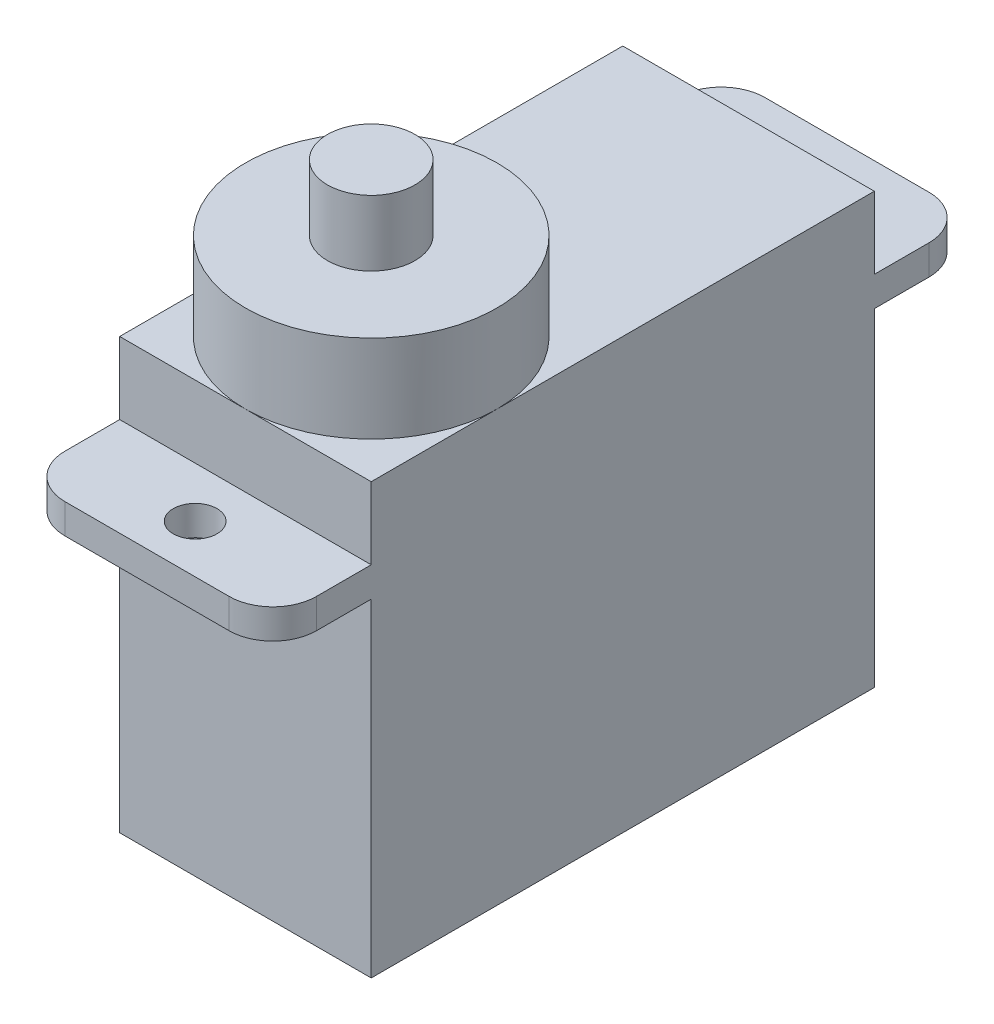
SolidWorks part; units mm, degrees
ref_plane "前视基准面" through (0, 0, 0) normal (0, 0, 1) x (1, 0, 0)
ref_plane "上视基准面" through (0, 0, 0) normal (0, 1, 0) x (1, 0, 0)
ref_plane "右视基准面" through (0, 0, 0) normal (1, 0, 0) x (0, 0, -1)
sketch "草图1" plane through (0, 0, 0) normal (0, 1, 0) x (1, 0, 0)
  line L1 (-5.75, 11.5) -> (5.75, 11.5)
  line L2 (-5.75, 11.5) -> (-5.75, -11.5)
  line L3 (-5.75, -11.5) -> (5.75, -11.5)
  line L4 (5.75, 11.5) -> (5.75, -11.5)
  line L5 (-5.75, 11.5) -> (5.75, -11.5) construction
  line L6 (-5.75, -11.5) -> (5.75, 11.5) construction
  point P0 (0, 0)
extrude "凸台-拉伸1" add sketch "草图1" along normal blind 19.65
ref_plane "基准面1" through (0, 15, 0) normal (0, -1, 0) x (-1, 0, 0)
sketch "草图3" plane through (0, 15, 0) normal (0, -1, 0) x (-1, 0, 0)
  line L1 (-5.75, -16) -> (5.75, -16)
  line L2 (-5.75, -16) -> (-5.75, 16)
  line L3 (-5.75, 16) -> (5.75, 16)
  line L4 (5.75, -16) -> (5.75, 16)
  line L5 (-5.75, -16) -> (5.75, 16) construction
  line L6 (-5.75, 16) -> (5.75, -16) construction
  point P0 (0, 0)
extrude "凸台-拉伸3" add sketch "草图3" against normal blind 1.36
sketch "草图4" plane through (0, 15, 0) normal (0, -1, 0) x (-1, 0, 0)
  circle A0 centre (0, 13.8) radius 1
  circle A1 centre (0, -13.8) radius 1
  dimension "D1" = 2
extrude "切除-拉伸1" cut sketch "草图4" against normal blind 5
fillet "圆角8" radius 2 4 edges at (-5.75, 15.68, -16) (5.75, 15.68, -16) (-5.75, 15.68, 16) (5.75, 15.68, 16)
sketch "草图9" plane through (0, 19.65, 0) normal (0, 1, 0) x (1, 0, 0)
  circle A0 centre (0, -5.75) radius 5.75
extrude "凸台-拉伸7" add sketch "草图9" along normal blind 4
sketch "草图10" plane through (0, 23.65, 0) normal (0, 1, 0) x (1, 0, 0)
  circle A0 centre (0, -5.75) radius 2
extrude "凸台-拉伸8" add sketch "草图10" along normal blind 3
